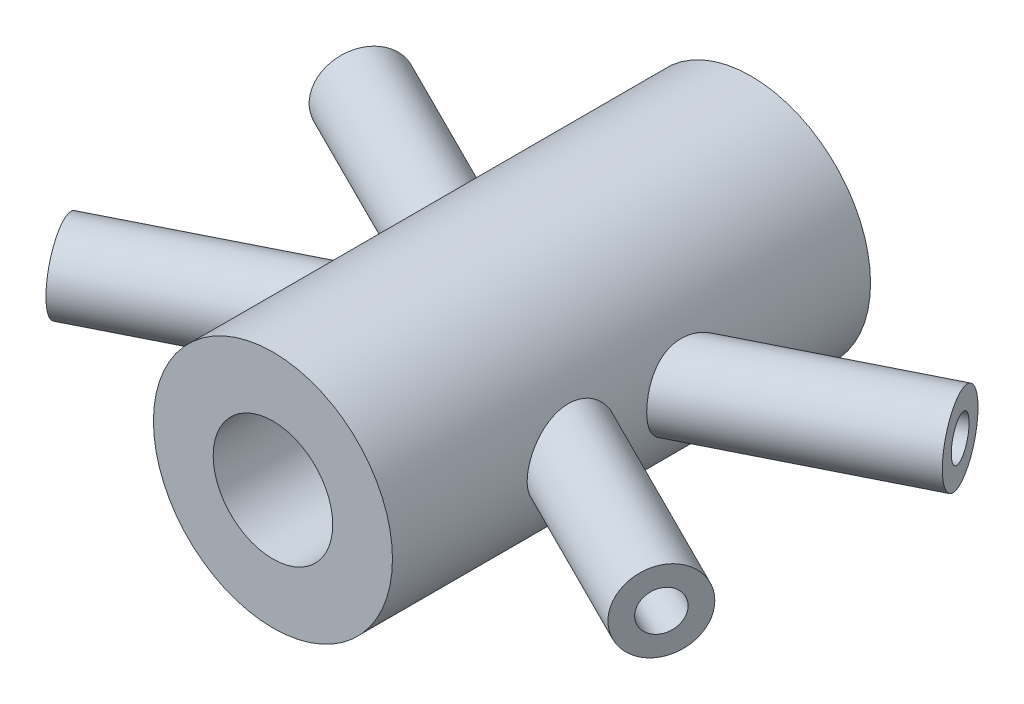
SolidWorks part; units mm, degrees
ref_plane "Alzado" through (0, 0, 0) normal (0, 0, 1) x (1, 0, 0)
ref_plane "Planta" through (0, 0, 0) normal (0, 1, 0) x (1, 0, 0)
ref_plane "Vista lateral" through (0, 0, 0) normal (1, 0, 0) x (0, 0, -1)
sketch "Croquis1" plane through (0, 0, 0) normal (0, 0, 1) x (1, 0, 0)
  circle A0 centre (0, 0) radius 60
extrude "Saliente-Extruir1" add sketch "Croquis1" along normal blind 240
sketch "Croquis3" plane through (0, 0, 0) normal (0, 1, 0) x (1, 0, 0)
  line L0 (0, -120) -> (150, -45)
  line L1 (-60, -240) -> (60, 0)
  line L2 (-60, 0) -> (60, -240)
  line L3 (150, -45) -> (-150, -195)
  line L4 (0, -120) -> (150, -195) construction
  line L5 (150, -195) -> (-150, -45) construction
  line L6 (150, -45) -> (127.5, 0) construction
  line L7 (127.5, 0) -> (172.8061, -90.6121) construction
  line L8 (150, -195) -> (127.5, -240) construction
  line L9 (127.5, -240) -> (172.8061, -149.3879) construction
  line L10 (-150, -45) -> (-126.4202, 2.1597) construction
  line L11 (-126.4202, 2.1597) -> (-173.9006, -92.8012) construction
  line L12 (-150, -195) -> (-127.5, -240) construction
  line L13 (-127.5, -240) -> (-172.8061, -149.3879) construction
  point P21 (0, 0)
  point P22 (0, 0)
  point P23 (0, 0)
  point P24 (0, 0)
  point P25 (0, 0)
ref_plane "Plano2" through (102, 0, -51) normal (0.8944, 0, -0.4472) x (-0.4472, 0, -0.8944)
ref_plane "Plano3" through (198, 0, 99) normal (0.8944, 0, 0.4472) x (0.4472, 0, -0.8944)
sketch "Croquis4" plane through (102, 0, -51) normal (0.8944, 0, -0.4472) x (-0.4472, 0, -0.8944)
  circle A0 centre (-107.3313, 0) radius 20
extrude "Saliente-Extruir2" add sketch "Croquis4" against normal up to vertex (335.4102 mm away) up to point (-150, 0, 195)
sketch "Croquis5" plane through (198, 0, 99) normal (0.8944, 0, 0.4472) x (0.4472, 0, -0.8944)
  circle A0 centre (-107.3313, 0) radius 20
extrude "Saliente-Extruir3" add sketch "Croquis5" against normal up to vertex (335.4102 mm away) up to point (-150, 0, 45)
sketch "Croquis6" plane through (198, 0, 99) normal (0.8944, 0, 0.4472) x (0.4472, 0, -0.8944)
  circle A0 centre (-107.3313, 0) radius 10
extrude "Cortar-Extruir2" cut sketch "Croquis6" against normal up to vertex (335.4102 mm away) up to point (-173.9006, 0, 92.8012)
sketch "Croquis7" plane through (102, 0, -51) normal (0.8944, 0, -0.4472) x (-0.4472, 0, -0.8944)
  circle A0 centre (-107.3313, 0) radius 10
extrude "Cortar-Extruir3" cut sketch "Croquis7" against normal up to vertex (335.4102 mm away) up to point (-150, 0, 195)
sketch "Croquis8" plane through (0, 0, 0) normal (0, 0, -1) x (-1, 0, 0)
  circle A0 centre (0, 0) radius 30
extrude "Cortar-Extruir4" cut sketch "Croquis8" against normal blind 304
